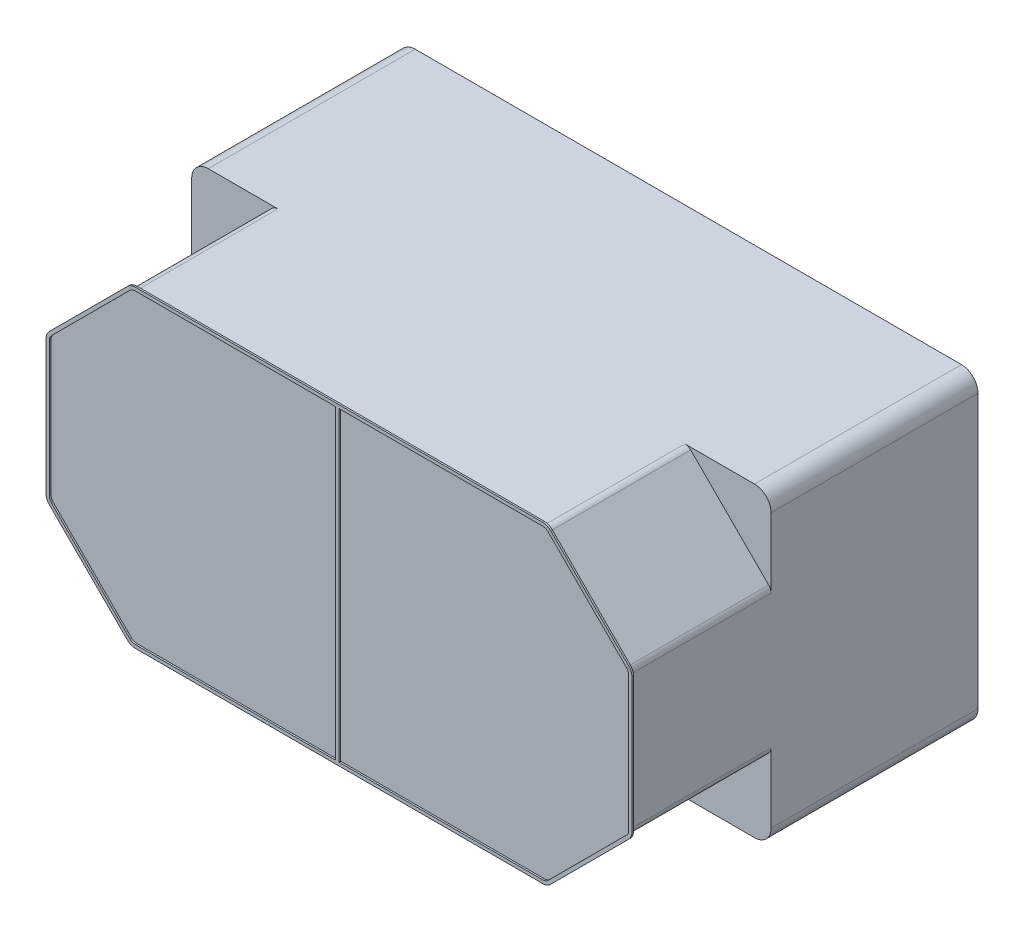
SolidWorks part; units mm, degrees
ref_plane "前视基准面" through (0, 0, 0) normal (0, 0, 1) x (1, 0, 0)
ref_plane "上视基准面" through (0, 0, 0) normal (0, 1, 0) x (1, 0, 0)
ref_plane "右视基准面" through (0, 0, 0) normal (1, 0, 0) x (0, 0, -1)
other "Configuration Table"
sketch "草图1" plane through (0, 0, 0) normal (0, 0, 1) x (1, 0, 0)
  line L1 (17.5, 91.7167) -> (-17.5, 91.7167)
  line L2 (17.5, 91.7167) -> (17.5, 110.2167)
  line L3 (17.5, 110.2167) -> (-17.5, 110.2167)
  line L4 (-17.5, 91.7167) -> (-17.5, 110.2167)
  line L5 (17.5, 91.7167) -> (-17.5, 110.2167) construction
  line L6 (17.5, 110.2167) -> (-17.5, 91.7167) construction
  point P0 (0, 100.9667)
  dimension "D1" = 35
  dimension "D2" = 18.5
extrude "凸台-拉伸1" add sketch "草图1" along normal blind 12.5
sketch "草图2" plane through (0, 0, 12.5) normal (0, 0, 1) x (1, 0, 0)
  line L0 (-12.5, 110.2167) -> (-17.5, 105.2167)
  line L1 (17.5, 105.2167) -> (12.5, 110.2167)
  line L2 (12.5, 91.7167) -> (17.5, 96.7167)
  line L3 (-17.5, 96.7167) -> (-12.5, 91.7167)
  line L4 (-17.5, 110.2167) -> (-17.5, 91.7167)
  line L5 (-17.5, 91.7167) -> (17.5, 91.7167)
  line L6 (17.5, 91.7167) -> (17.5, 110.2167)
  line L7 (17.5, 110.2167) -> (-17.5, 110.2167)
  line L8 (-17.5, 105.2167) -> (-17.5, 96.7167)
  line L9 (-12.5, 91.7167) -> (12.5, 91.7167)
  line L10 (17.5, 96.7167) -> (17.5, 105.2167)
  line L11 (12.5, 110.2167) -> (-12.5, 110.2167)
  dimension "D1" = 0
extrude "凸台-拉伸2" add sketch "草图2" along normal blind 8.5
fillet "圆角1" radius 1 4 edges at (17.5, 110.2167, 6.25) (17.5, 91.7167, 6.25) (-17.5, 91.7167, 6.25) (-17.5, 110.2167, 6.25)
fillet "圆角2" radius 0.5 8 edges at (17.5, 96.7167, 16.75) (12.5, 91.7167, 16.75) (-12.5, 91.7167, 16.75) (12.5, 110.2167, 16.75) (-12.5, 110.2167, 16.75) (17.5, 105.2167, 16.75) (-17.5, 96.7167, 16.75) (-17.5, 105.2167, 16.75)
sketch "草图3" plane through (0, 0, 0) normal (0, 0, -1) x (-1, 0, 0)
  line L0 (0, 91.7167) -> (0, 110.2167) construction
  line L1 (17.5, 100.9667) -> (-17.5, 100.9667) construction
  line L3 (-14, 106.7167) -> (14, 106.7167) construction
  line L4 (16.5, 110.2167) -> (-16.5, 110.2167)
  line L5 (-17.5, 109.2167) -> (-17.5, 92.7167)
  line L6 (-16.5, 91.7167) -> (16.5, 91.7167)
  line L7 (17.5, 92.7167) -> (17.5, 109.2167)
  line L8 (16.5, 110.2167) -> (-16.5, 110.2167) construction
  line L9 (-17.5, 109.2167) -> (-17.5, 92.7167) construction
  line L10 (-16.5, 91.7167) -> (16.5, 91.7167) construction
  line L11 (17.5, 92.7167) -> (17.5, 109.2167) construction
  line L12 (-14, 106.7167) -> (-14, 95.2167) construction
  line L13 (-14, 95.2167) -> (14, 95.2167) construction
  line L14 (14, 106.7167) -> (14, 95.2167) construction
  line L15 (-14, 106.7167) -> (14, 95.2167) construction
  line L16 (-14, 95.2167) -> (14, 106.7167) construction
  circle A0 centre (14, 95.2167) radius 1
  circle A1 centre (-14, 106.7167) radius 1
  arc A4 (-16.5, 110.2167) -> (-17.5, 109.2167) centre (-16.5, 109.2167) ccw
  arc A5 (-17.5, 92.7167) -> (-16.5, 91.7167) centre (-16.5, 92.7167) ccw
  arc A6 (16.5, 91.7167) -> (17.5, 92.7167) centre (16.5, 92.7167) ccw
  arc A7 (17.5, 109.2167) -> (16.5, 110.2167) centre (16.5, 109.2167) ccw
  arc A8 (-16.5, 110.2167) -> (-17.5, 109.2167) centre (-16.5, 109.2167) ccw construction
  arc A9 (-17.5, 92.7167) -> (-16.5, 91.7167) centre (-16.5, 92.7167) ccw construction
  arc A10 (16.5, 91.7167) -> (17.5, 92.7167) centre (16.5, 92.7167) ccw construction
  arc A11 (17.5, 109.2167) -> (16.5, 110.2167) centre (16.5, 109.2167) ccw construction
  point P15 (0, 100.9667)
  dimension "D4" = 2
  dimension "D5" = 2
  dimension "D2" = 28
  dimension "D3" = 11.5
  dimension "D1" = 0
extrude "切除-拉伸1" cut sketch "草图3" against normal blind 4
sketch "草图4" plane through (0, 91.7167, 0) normal (0, -1, 0) x (1, 0, 0)
  line L0 (0, 0) -> (0, 16.2712) construction
  line L2 (3.9, 3.7) -> (-3.9, 3.7)
  line L3 (3.9, 3.7) -> (3.9, 0)
  line L4 (3.9, 0) -> (-3.9, 0)
  line L5 (-3.9, 3.7) -> (-3.9, 0)
  line L6 (3.9, 3.7) -> (-3.9, 0) construction
  line L7 (3.9, 0) -> (-3.9, 3.7) construction
  line L8 (16.5, 12.5) -> (12.2929, 12.5)
  line L9 (12.2929, 12.5) -> (12.2929, 21)
  line L10 (12.2929, 21) -> (-12.2929, 21)
  line L11 (-12.2929, 21) -> (-12.2929, 12.5)
  line L12 (-12.2929, 12.5) -> (-16.5, 12.5)
  line L13 (-16.5, 12.5) -> (-16.5, 0)
  line L14 (-16.5, 0) -> (16.5, 0)
  line L15 (16.5, 0) -> (16.5, 12.5)
  line L16 (16.5, 12.5) -> (12.2929, 12.5) construction
  line L17 (12.2929, 12.5) -> (12.2929, 21) construction
  line L18 (12.2929, 21) -> (-12.2929, 21) construction
  line L19 (-12.2929, 21) -> (-12.2929, 12.5) construction
  line L20 (-12.2929, 12.5) -> (-16.5, 12.5) construction
  line L21 (-16.5, 12.5) -> (-16.5, 0) construction
  line L22 (-16.5, 0) -> (16.5, 0) construction
  line L23 (16.5, 0) -> (16.5, 12.5) construction
  point P6 (0, 1.85)
  dimension "D2" = 3.7
  dimension "D3" = 7.8
  dimension "D1" = 0
extrude "凸台-拉伸3" add sketch "草图4" along normal blind 7.5
sketch "草图5" plane through (0, 0, 21) normal (0, 0, 1) x (1, 0, 0)
  line L4 (0, 110.2167) -> (0, 91.7167)
  line L16 (12.6464, 91.8631) -> (17.3536, 96.5702)
  line L17 (17.5, 96.9238) -> (17.5, 105.0096)
  line L18 (17.3536, 105.3631) -> (12.6464, 110.0702)
  line L19 (12.2929, 110.2167) -> (-12.2929, 110.2167)
  line L20 (-12.6464, 110.0702) -> (-17.3536, 105.3631)
  line L21 (-17.5, 105.0096) -> (-17.5, 96.9238)
  line L22 (-17.3536, 96.5702) -> (-12.6464, 91.8631)
  line L23 (-12.2929, 91.7167) -> (12.2929, 91.7167)
  line L24 (12.6464, 91.8631) -> (17.3536, 96.5702)
  line L25 (17.5, 96.9238) -> (17.5, 105.0096)
  line L26 (17.3536, 105.3631) -> (12.6464, 110.0702)
  line L27 (12.2929, 110.2167) -> (-12.2929, 110.2167)
  line L28 (-12.6464, 110.0702) -> (-17.3536, 105.3631)
  line L29 (-17.5, 105.0096) -> (-17.5, 96.9238)
  line L30 (-17.3536, 96.5702) -> (-12.6464, 91.8631)
  line L31 (-12.2929, 91.7167) -> (12.2929, 91.7167)
  arc A8 (17.3536, 96.5702) -> (17.5, 96.9238) centre (17, 96.9238) ccw
  arc A9 (17.5, 105.0096) -> (17.3536, 105.3631) centre (17, 105.0096) ccw
  arc A10 (12.6464, 110.0702) -> (12.2929, 110.2167) centre (12.2929, 109.7167) ccw
  arc A11 (-12.2929, 110.2167) -> (-12.6464, 110.0702) centre (-12.2929, 109.7167) ccw
  arc A12 (-17.3536, 105.3631) -> (-17.5, 105.0096) centre (-17, 105.0096) ccw
  arc A13 (-17.5, 96.9238) -> (-17.3536, 96.5702) centre (-17, 96.9238) ccw
  arc A14 (-12.6464, 91.8631) -> (-12.2929, 91.7167) centre (-12.2929, 92.2167) ccw
  arc A15 (12.2929, 91.7167) -> (12.6464, 91.8631) centre (12.2929, 92.2167) ccw
  arc A16 (17.3536, 96.5702) -> (17.5, 96.9238) centre (17, 96.9238) ccw
  arc A17 (17.5, 105.0096) -> (17.3536, 105.3631) centre (17, 105.0096) ccw
  arc A18 (12.6464, 110.0702) -> (12.2929, 110.2167) centre (12.2929, 109.7167) ccw
  arc A19 (-12.2929, 110.2167) -> (-12.6464, 110.0702) centre (-12.2929, 109.7167) ccw
  arc A20 (-17.3536, 105.3631) -> (-17.5, 105.0096) centre (-17, 105.0096) ccw
  arc A21 (-17.5, 96.9238) -> (-17.3536, 96.5702) centre (-17, 96.9238) ccw
  arc A22 (-12.6464, 91.8631) -> (-12.2929, 91.7167) centre (-12.2929, 92.2167) ccw
  arc A23 (12.2929, 91.7167) -> (12.6464, 91.8631) centre (12.2929, 92.2167) ccw
  dimension "D1" = 0
extrude "拉伸-薄壁3" add sketch "草图5" along normal blind 0.1 separate body thin contours L27 A19 L28 A20 L29 A21 L30 A22 L31 A23 L24 A16 L25 A17 L26 A18 | L4
